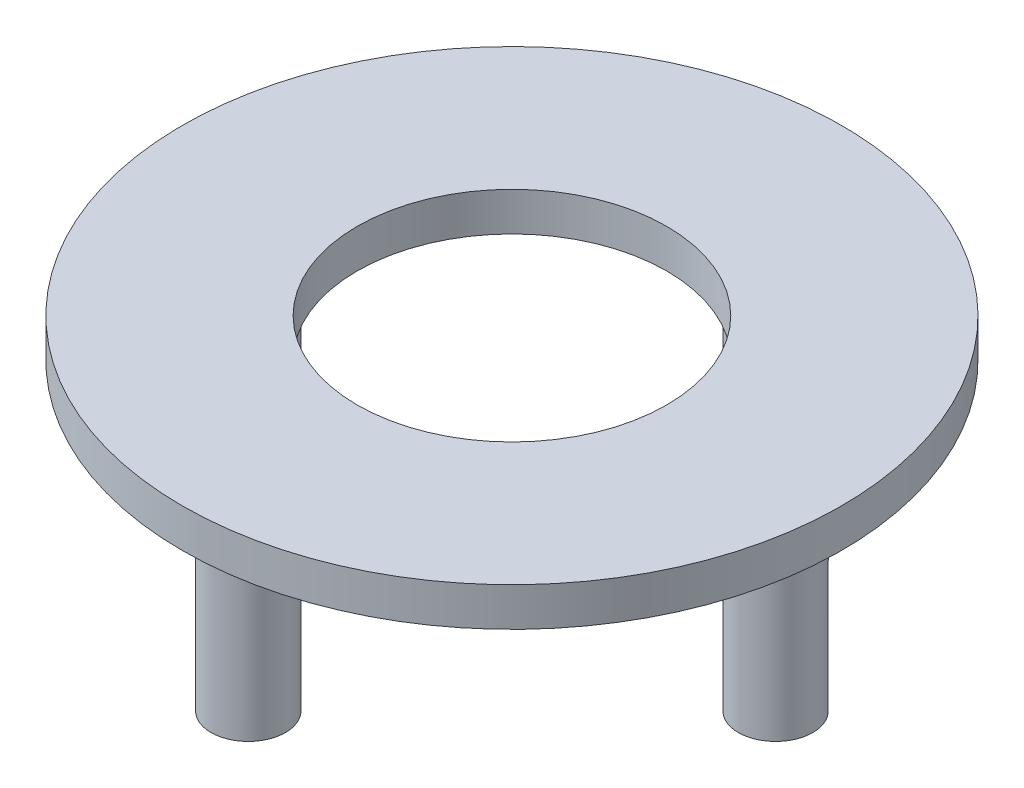
SolidWorks part; units mm, degrees
ref_plane "前基準面" through (0, 0, 0) normal (0, 0, 1) x (1, 0, 0)
ref_plane "上基準面" through (0, 0, 0) normal (0, 1, 0) x (1, 0, 0)
ref_plane "右基準面" through (0, 0, 0) normal (1, 0, 0) x (0, 0, -1)
sketch "草圖1" plane through (0, 0, 0) normal (0, 1, 0) x (1, 0, 0)
  circle A0 centre (0, 0) radius 57.5
  circle A1 centre (0, 0) radius 27
  dimension "D1" = 115
  dimension "D2" = 54
extrude "填料-伸長2" add sketch "草圖1" along normal blind 6.75
sketch "草圖4" plane through (0, 6.75, 0) normal (0, 1, 0) x (1, 0, 0)
  circle A0 centre (0, 46) radius 5
  circle A1 centre (46, 0) radius 5
  circle A2 centre (-46, 0) radius 5
  circle A3 centre (0, -46) radius 5
  dimension "D1" = 10
  dimension "D2" = 10
  dimension "D3" = 46
  dimension "D6" = 46
  dimension "D4" = 46
  dimension "D5" = 46
sketch "草圖3" plane through (0, 0, 0) normal (0, -1, 0) x (1, 0, 0)
  circle A0 centre (0, 46) radius 6.5
  circle A1 centre (0, -46) radius 6.5
  circle A2 centre (-46, 0) radius 6.5
  circle A3 centre (46, 0) radius 6.5
  dimension "D1" = 13
  dimension "D2" = 46
  dimension "D4" = 13
  dimension "D3" = 92
  dimension "D5" = 46
  dimension "D6" = 92
extrude "填料-伸長3" add sketch "草圖3" along normal blind 30
extrude "除料-伸長1" [suppressed] cut sketch "草圖4" against normal through all
ref_plane "平面1" through (0, -0.45, 0) normal (0, 1, 0) x (1, 0, 0)
sketch "草圖5" plane through (0, -0.45, 0) normal (0, 1, 0) x (1, 0, 0)
  circle A0 centre (0, 0) radius 80
  dimension "D1" = 160
